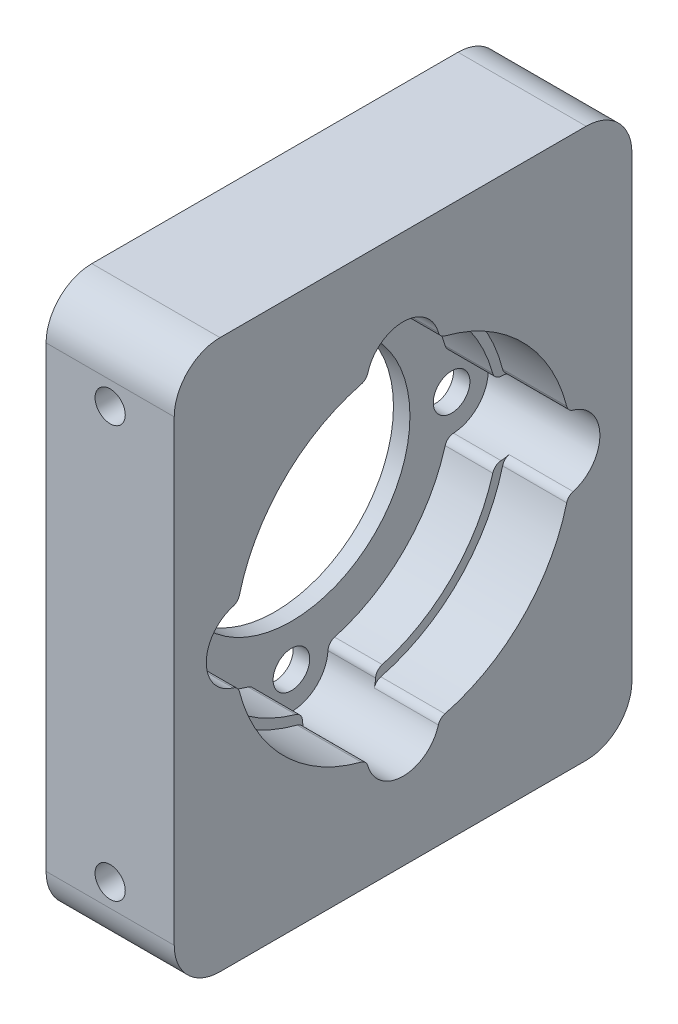
SolidWorks part; units mm, degrees
material "5052-H34"
ref_plane "正面" through (0, 0, 0) normal (0, 0, 1) x (1, 0, 0)
ref_plane "平面" through (0, 0, 0) normal (0, 1, 0) x (1, 0, 0)
ref_plane "右側面" through (0, 0, 0) normal (1, 0, 0) x (0, 0, -1)
sketch "ｽｹｯﾁ1" plane through (0, 0, 0) normal (1, 0, 0) x (0, 0, -1)
  line L0 (0, 0) -> (0, 15) construction
  line L2 (-25, 30) -> (25, 30)
  line L3 (-25, 30) -> (-25, 0)
  line L4 (-25, 0) -> (25, 0)
  line L5 (25, 30) -> (25, 0)
  line L6 (-25, 30) -> (25, 0) construction
  line L7 (-25, 0) -> (25, 30) construction
  circle A0 centre (0, 0) radius 25
  dimension "D1" = 50
  dimension "D2" = 30
  dimension "D3" = 50
extrude "ﾎﾞｽ - 押し出し1" add sketch "ｽｹｯﾁ1" along normal blind 15 contours A0 L4 L5 L2 L3 | L4 A0 | L4 A0
sketch "ｽｹｯﾁ2" plane through (15, 0, 0) normal (1, 0, 0) x (0, 0, -1)
  circle A0 centre (0, 0) radius 12.95
  dimension "D1" = 25.9
extrude "ｶｯﾄ - 押し出し1" cut sketch "ｽｹｯﾁ2" against normal through all
sketch "ｽｹｯﾁ3" plane through (15, 0, 0) normal (1, 0, 0) x (0, 0, -1)
  circle A0 centre (0, 0) radius 18.45
  dimension "D1" = 36.9
extrude "ｶｯﾄ - 押し出し2" cut sketch "ｽｹｯﾁ3" against normal blind 8
sketch "ｽｹｯﾁ4" plane through (7, 0, 0) normal (1, 0, 0) x (0, 0, -1)
  circle A0 centre (0, 0) radius 17.45
  circle A1 centre (0, 0) radius 18.45 construction
  dimension "D1" = 1
extrude "ｶｯﾄ - 押し出し3" cut sketch "ｽｹｯﾁ4" against normal blind 5.2
sketch "ｽｹｯﾁ5" plane through (1.8, 0, 0) normal (1, 0, 0) x (0, 0, -1)
  line L0 (0, 0) -> (0, 17.5) construction
  circle A0 centre (0, 0) radius 17.5 construction
  circle A1 centre (0, 17.5) radius 2
  circle A2 centre (17.5, 0) radius 2
  circle A3 centre (0, -17.5) radius 2
  circle A4 centre (-17.5, 0) radius 2
  dimension "D1" = 35
  dimension "D2" = 4
  dimension "D3" = 4
extrude "ｶｯﾄ - 押し出し4" cut sketch "ｽｹｯﾁ5" against normal through all both and the other way through all
sketch "ｽｹｯﾁ6" plane through (15, 0, 0) normal (1, 0, 0) x (0, 0, -1)
  line L7 (25, 0) -> (25, 30)
  line L8 (25, 30) -> (-25, 30)
  line L9 (-25, 30) -> (-25, 0)
  line L12 (25, 0) -> (25, 30)
  line L13 (25, 30) -> (-25, 30)
  line L14 (-25, 30) -> (-25, 0)
  arc A0 (1.8049, 18.3615) -> (-1.8049, 18.3615) centre (0, 17.5) ccw construction
  arc A1 (-25, 0) -> (25, 0) centre (0, 0) ccw
  arc A2 (-25, 0) -> (25, 0) centre (0, 0) ccw
  arc A3 (1.8049, 18.3615) -> (-1.8049, 18.3615) centre (0, 17.5) ccw
  circle A4 centre (0, 17.5) radius 4
  circle A5 centre (17.5, 0) radius 4
  circle A6 centre (0, -17.5) radius 4
  circle A7 centre (-17.5, 0) radius 4
  arc A8 (-1.8049, -18.3615) -> (1.8049, -18.3615) centre (0, -17.5) ccw construction
  arc A9 (-1.8049, -18.3615) -> (1.8049, -18.3615) centre (0, -17.5) ccw
  arc A10 (1.9932, 17.3358) -> (1.8049, 18.3615) centre (0, 17.5) ccw construction
  arc A11 (17.3358, 1.9932) -> (1.9932, 17.3358) centre (0, 0) ccw construction
  arc A12 (18.3615, 1.8049) -> (17.3358, 1.9932) centre (17.5, 0) ccw construction
  arc A13 (18.3615, 1.8049) -> (1.8049, 18.3615) centre (0, 0) ccw construction
  arc A14 (17.3358, -1.9932) -> (18.3615, -1.8049) centre (17.5, 0) ccw construction
  arc A15 (1.9932, -17.3358) -> (17.3358, -1.9932) centre (0, 0) ccw construction
  arc A16 (1.8049, -18.3615) -> (1.9932, -17.3358) centre (0, -17.5) ccw construction
  arc A17 (1.8049, -18.3615) -> (18.3615, -1.8049) centre (0, 0) ccw construction
  arc A18 (-1.9932, -17.3358) -> (-1.8049, -18.3615) centre (0, -17.5) ccw construction
  arc A19 (-17.3358, -1.9932) -> (-1.9932, -17.3358) centre (0, 0) ccw construction
  arc A20 (-18.3615, -1.8049) -> (-17.3358, -1.9932) centre (-17.5, 0) ccw construction
  arc A21 (-18.3615, -1.8049) -> (-1.8049, -18.3615) centre (0, 0) ccw construction
  arc A22 (-1.8049, 18.3615) -> (-1.9932, 17.3358) centre (0, 17.5) ccw construction
  arc A23 (-1.8049, 18.3615) -> (-18.3615, 1.8049) centre (0, 0) ccw construction
  arc A24 (-17.3358, 1.9932) -> (-18.3615, 1.8049) centre (-17.5, 0) ccw construction
  arc A25 (-1.9932, 17.3358) -> (-17.3358, 1.9932) centre (0, 0) ccw construction
  arc A26 (1.9932, 17.3358) -> (1.8049, 18.3615) centre (0, 17.5) ccw
  arc A27 (17.3358, 1.9932) -> (1.9932, 17.3358) centre (0, 0) ccw
  arc A28 (18.3615, 1.8049) -> (17.3358, 1.9932) centre (17.5, 0) ccw
  arc A29 (18.3615, 1.8049) -> (1.8049, 18.3615) centre (0, 0) ccw
  arc A30 (17.3358, -1.9932) -> (18.3615, -1.8049) centre (17.5, 0) ccw
  arc A31 (1.9932, -17.3358) -> (17.3358, -1.9932) centre (0, 0) ccw
  arc A32 (1.8049, -18.3615) -> (1.9932, -17.3358) centre (0, -17.5) ccw
  arc A33 (1.8049, -18.3615) -> (18.3615, -1.8049) centre (0, 0) ccw
  arc A34 (-1.9932, -17.3358) -> (-1.8049, -18.3615) centre (0, -17.5) ccw
  arc A35 (-17.3358, -1.9932) -> (-1.9932, -17.3358) centre (0, 0) ccw
  arc A36 (-18.3615, -1.8049) -> (-17.3358, -1.9932) centre (-17.5, 0) ccw
  arc A37 (-18.3615, -1.8049) -> (-1.8049, -18.3615) centre (0, 0) ccw
  arc A38 (-1.8049, 18.3615) -> (-1.9932, 17.3358) centre (0, 17.5) ccw
  arc A39 (-1.8049, 18.3615) -> (-18.3615, 1.8049) centre (0, 0) ccw
  arc A40 (-17.3358, 1.9932) -> (-18.3615, 1.8049) centre (-17.5, 0) ccw
  arc A41 (-1.9932, 17.3358) -> (-17.3358, 1.9932) centre (0, 0) ccw
  arc M7 (-1.8049, 18.3615) -> (1.8049, 18.3615) centre (0, 17.5) cw
  arc M8 (1.8049, 18.3615) -> (18.3615, 1.8049) centre (0, 0) cw
  arc M9 (18.3615, 1.8049) -> (18.3615, -1.8049) centre (17.5, 0) cw
  arc M10 (18.3615, -1.8049) -> (1.8049, -18.3615) centre (0, 0) cw
  arc M11 (1.8049, -18.3615) -> (-1.8049, -18.3615) centre (0, -17.5) cw
  arc M12 (-1.8049, -18.3615) -> (-18.3615, -1.8049) centre (0, 0) cw
  arc M13 (-18.3615, -1.8049) -> (-18.3615, 1.8049) centre (-17.5, 0) cw
  arc M14 (-18.3615, 1.8049) -> (-1.8049, 18.3615) centre (0, 0) cw
  dimension "D2" = 8
  dimension "D1" = 0
  dimension "D3" = 4
extrude "ｶｯﾄ - 押し出し5" cut sketch "ｽｹｯﾁ6" against normal blind 13.2 contours A7 M14 M12 M13 | A4 M8 M14 M7 | A5 M10 M8 M9 | A6 M12 M10 M11 | A41 A7 A40 M14 | A36 A7 A35 M12 | A32 A6 A31 M10 | A35 A6 A34 M12 | A31 A5 A30 M10 | A28 A5 A27 M8 | A41 A38 A4 M14 | A27 A4 A26 M8
sketch "ｽｹｯﾁ8" plane through (15, 0, 0) normal (1, 0, 0) x (0, 0, -1)
  line L7 (25, 0) -> (25, 30)
  line L8 (25, 30) -> (-25, 30)
  line L9 (-25, 30) -> (-25, 0)
  line L12 (25, 0) -> (25, 30)
  line L13 (25, 30) -> (-25, 30)
  line L14 (-25, 30) -> (-25, 0)
  arc A1 (-25, 0) -> (25, 0) centre (0, 0) ccw
  arc A2 (-25, 0) -> (25, 0) centre (0, 0) ccw
  dimension "D1" = 0
extrude "ｶｯﾄ - 押し出し7" cut sketch "ｽｹｯﾁ8" against normal blind 1
sketch "ｽｹｯﾁ12" plane through (0, 0, 0) normal (-1, 0, 0) x (0, 0, 1)
  line L0 (25, 30) -> (25, 0) construction
  line L1 (-25, 0) -> (25, 0)
  line L2 (-25, 0) -> (-25, -30)
  line L3 (-25, -30) -> (25, -30)
  line L4 (25, 0) -> (25, -30)
  line L8 (25, 0) -> (25, 30)
  line L9 (25, 30) -> (-25, 30)
  line L10 (-25, 30) -> (-25, 0)
  line L11 (25, 0) -> (25, 30)
  line L12 (25, 30) -> (-25, 30)
  line L13 (-25, 30) -> (-25, 0)
  circle A1 centre (0, 0) radius 12.95
  circle A2 centre (0, 0) radius 12.95
  circle A3 centre (17.5, 0) radius 2
  circle A4 centre (17.5, 0) radius 2
  circle A5 centre (0, -17.5) radius 2
  circle A6 centre (0, -17.5) radius 2
  circle A7 centre (-17.5, 0) radius 2
  circle A8 centre (-17.5, 0) radius 2
  circle A9 centre (0, 17.5) radius 2
  circle A10 centre (0, 17.5) radius 2
  arc A11 (-25, 0) -> (25, 0) centre (0, 0) ccw
  arc A12 (-25, 0) -> (25, 0) centre (0, 0) ccw
  arc M19 (-25, 0) -> (25, 0) centre (0, 0) ccw
  dimension "D1" = 30
  dimension "D2" = 0
  dimension "D3" = 0
  dimension "D4" = 0
  dimension "D5" = 0
  dimension "D6" = 0
  dimension "D7" = 0
extrude "ﾎﾞｽ - 押し出し2" add sketch "ｽｹｯﾁ12" against normal blind 14 contours L4 L2 L3 M19
sketch "ｽｹｯﾁ13" plane through (0, 0, 25) normal (0, 0, 1) x (1, 0, 0)
  line L0 (7, -30) -> (7, -22.5) construction
  line L1 (14, -30) -> (0, -30) construction
  line L2 (7, -22.5) -> (7, 22.5) construction
  circle A0 centre (7, -22.5) radius 1.65
  circle A1 centre (7, 22.5) radius 1.65
  dimension "D1" = 3.3
  dimension "D2" = 7.5
  dimension "D3" = 45
extrude "ｶｯﾄ - 押し出し11" cut sketch "ｽｹｯﾁ13" against normal blind 10
ref_plane "平面4" through (0, 0, 0) normal (0, 0, 1) x (1, 0, 0)
mirror "ﾐﾗｰ4" about plane through (0, 0, 0) normal (0, 0, 1) of "ｶｯﾄ - 押し出し11"
fillet "ﾌｨﾚｯﾄ1" radius 5 4 edges at (7, -30, -25) (7, -30, 25) (7, 30, -25) (7, 30, 25)
fillet "ﾌｨﾚｯﾄ2" radius 1 16 edges at (10.5, -18.0186, -3.9662) (10.5, -18.0186, 3.9662) (4.4, -16.9929, -3.9677) (4.4, -16.9929, 3.9677) (10.5, 3.9662, -18.0186) (10.5, -3.9662, -18.0186) (4.4, 3.9677, -16.9929) (4.4, -3.9677, -16.9929) (10.5, 18.0186, 3.9662) (10.5, 18.0186, -3.9662) (4.4, 16.9929, 3.9677) (4.4, 16.9929, -3.9677) (4.4, -3.9677, 16.9929) (4.4, 3.9677, 16.9929) (10.5, -3.9662, 18.0186) (10.5, 3.9662, 18.0186)
